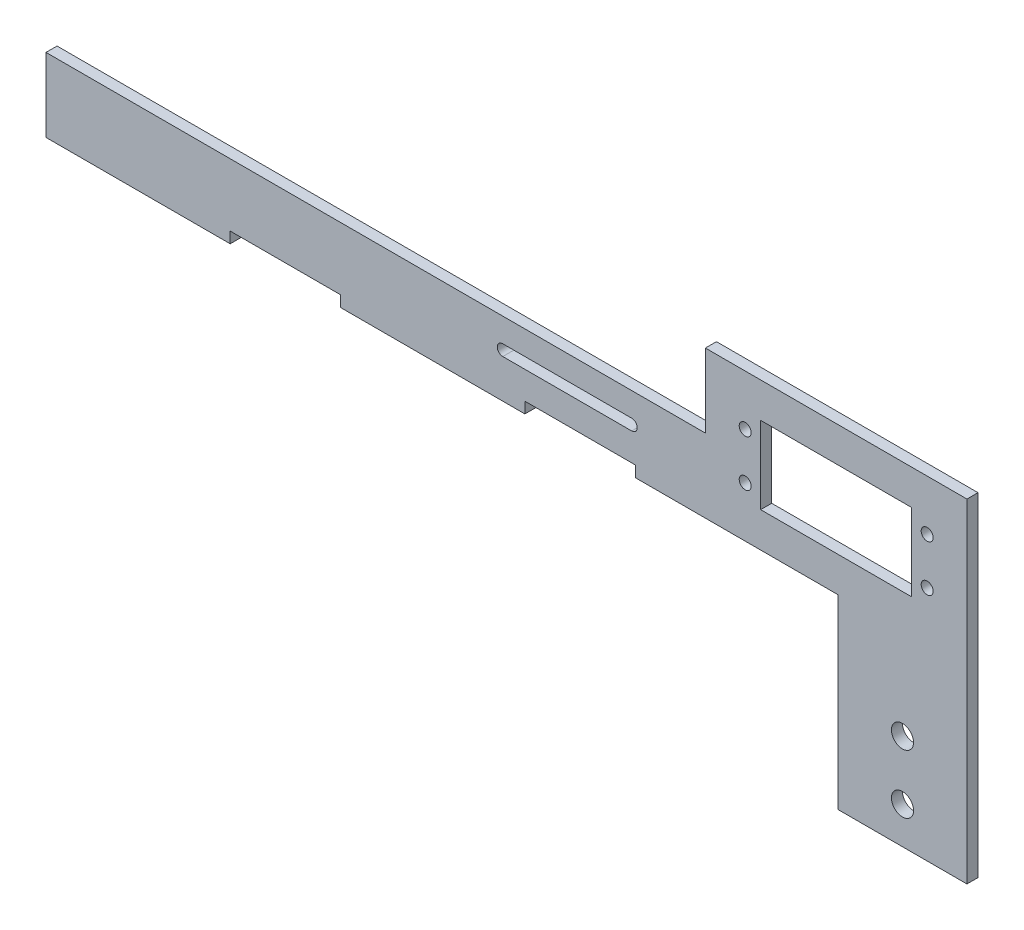
SolidWorks part; units mm, degrees
ref_plane "Plano frontal" through (0, 0, 0) normal (0, 0, 1) x (1, 0, 0)
ref_plane "Plano superior" through (0, 0, 0) normal (0, 1, 0) x (1, 0, 0)
ref_plane "Plano direito" through (0, 0, 0) normal (1, 0, 0) x (0, 0, -1)
sketch "Esboço1" plane through (0, 0, 0) normal (0, 0, 1) x (1, 0, 0)
  line L0 (194, 0) -> (235, 0) construction
  line L1 (215, -20) -> (160, -20)
  line L2 (250, -20) -> (250, 20)
  line L3 (250, 20) -> (179, 20)
  line L4 (0, -20) -> (0, 0)
  line L5 (194, 10.5) -> (235, 10.5)
  line L6 (194, 10.5) -> (194, -10.5)
  line L7 (194, -10.5) -> (235, -10.5)
  line L8 (235, 10.5) -> (235, -10.5)
  line L9 (214.5, 10.5) -> (214.5, -10.5) construction
  line L10 (0, 0) -> (179, 0)
  line L11 (179, 0) -> (179, 20)
  line L12 (250, 0) -> (184.4373, 0) construction
  line L13 (50, -20) -> (50, -17)
  line L14 (50, -17) -> (80, -17)
  line L15 (80, -17) -> (80, -20)
  line L16 (130, -20) -> (130, -17)
  line L17 (130, -17) -> (160, -17)
  line L18 (160, -17) -> (160, -20)
  line L19 (50, -20) -> (0, -20)
  line L20 (130, -20) -> (80, -20)
  line L21 (124, -8) -> (159, -8) construction
  line L22 (124, -6.5) -> (159, -6.5)
  line L23 (124, -9.5) -> (159, -9.5)
  line L26 (215, -20) -> (215, -70.5)
  line L27 (215, -70.5) -> (250, -70.5)
  line L28 (250, -20) -> (250, -70.5)
  circle A0 centre (189.8, 6.3) radius 1.625
  circle A1 centre (239.2, 6.3) radius 1.625
  circle A2 centre (239.2, -6.3) radius 1.625
  circle A3 centre (189.8, -6.3) radius 1.625
  arc A5 (124, -6.5) -> (124, -9.5) centre (124, -8) ccw
  arc A6 (159, -9.5) -> (159, -6.5) centre (159, -8) ccw
  circle A7 centre (232.5, -60.5) radius 3
  circle A8 centre (232.5, -44.5) radius 3
  point P36 (141.5, -8)
  dimension "D8" = 3.25
  dimension "D9" = 4.2
  dimension "D19" = 1.5
  dimension "D27" = 6
  dimension "D29" = 10
  dimension "D30" = 6
  dimension "D3" = 41
  dimension "D4" = 15
  dimension "D5" = 21
  dimension "D6" = 9.5
  dimension "D7" = 4.2
  dimension "D10" = 20
  dimension "D11" = 15
  dimension "D12" = 179
  dimension "D13" = 50
  dimension "D14" = 30
  dimension "D15" = 3
  dimension "D16" = 50
  dimension "D17" = 30
  dimension "D18" = 3
  dimension "D20" = 8
  dimension "D21" = 35
  dimension "D22" = 20
  dimension "D23" = 71
  dimension "D24" = 40
  dimension "D25" = 9.5
  dimension "D26" = 35
  dimension "D28" = 50.5
  dimension "D31" = 16
extrude "Ressalto-extrusão1" add sketch "Esboço1" along normal blind 3 contours L20 L16 L17 L18 L1 L2 L3 L11 L10 L4 L19 L13 L14 L15 A1 A0 L5 L8 L7 L6 A2 A3
